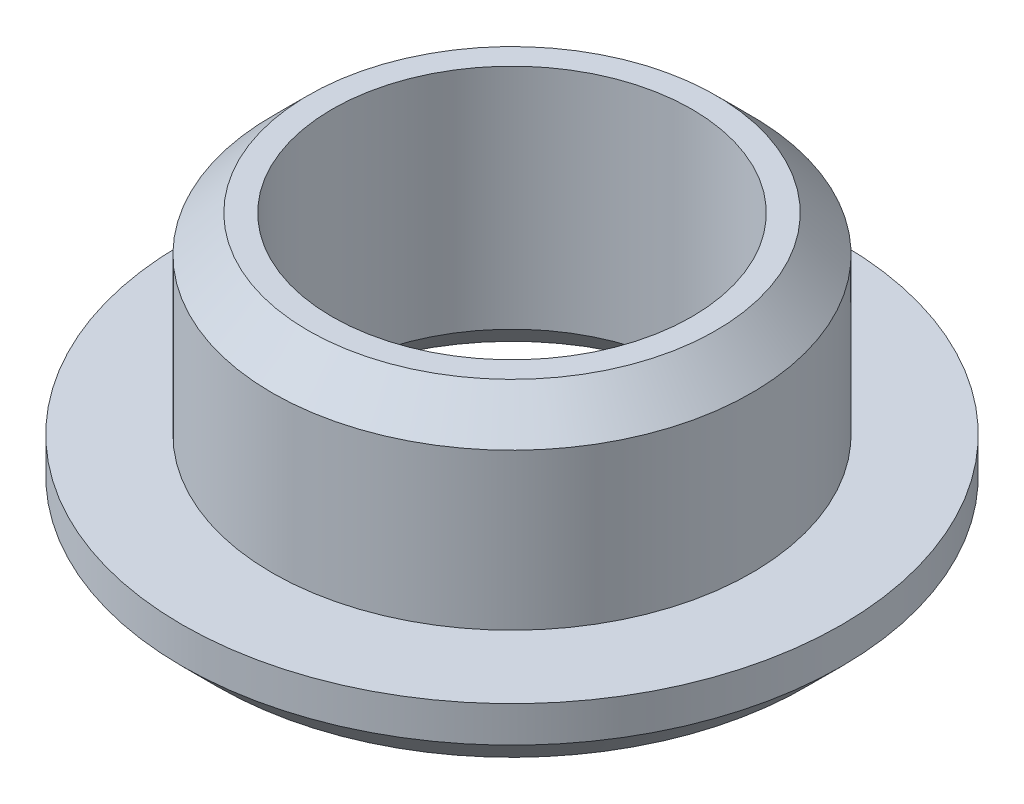
SolidWorks part; units mm, degrees
ref_plane "Front Plane" through (0, 0, 0) normal (0, 0, 1) x (1, 0, 0)
ref_plane "Top Plane" through (0, 0, 0) normal (0, 1, 0) x (1, 0, 0)
ref_plane "Right Plane" through (0, 0, 0) normal (1, 0, 0) x (0, 0, -1)
sketch "Sketch2" plane through (0, 0, 0) normal (0, 1, 0) x (1, 0, 0)
  circle A0 centre (0, 0) radius 7.5
  circle A1 centre (0, 0) radius 10
  dimension "D1" = 15
  dimension "D2" = 20
extrude "Boss-Extrude1" add sketch "Sketch2" along normal blind 8
sketch "Sketch3" plane through (0, 0, 0) normal (0, 1, 0) x (1, 0, 0)
  circle A0 centre (0, 0) radius 10 construction
  circle A1 centre (0, 0) radius 10
  circle A2 centre (0, 0) radius 13.75
  circle A3 centre (0, 0) radius 7.5 construction
  circle A4 centre (0, 0) radius 7.5
  dimension "D1" = 27.5
extrude "Boss-Extrude2" add sketch "Sketch3" against normal blind 3 contours A1 A4 | A2 A1
chamfer "Chamfer1" distance 1.5 angle 45 3 edges at (0, -3, 7.5) (0, 8, 10) (0, -3, 13.75)
